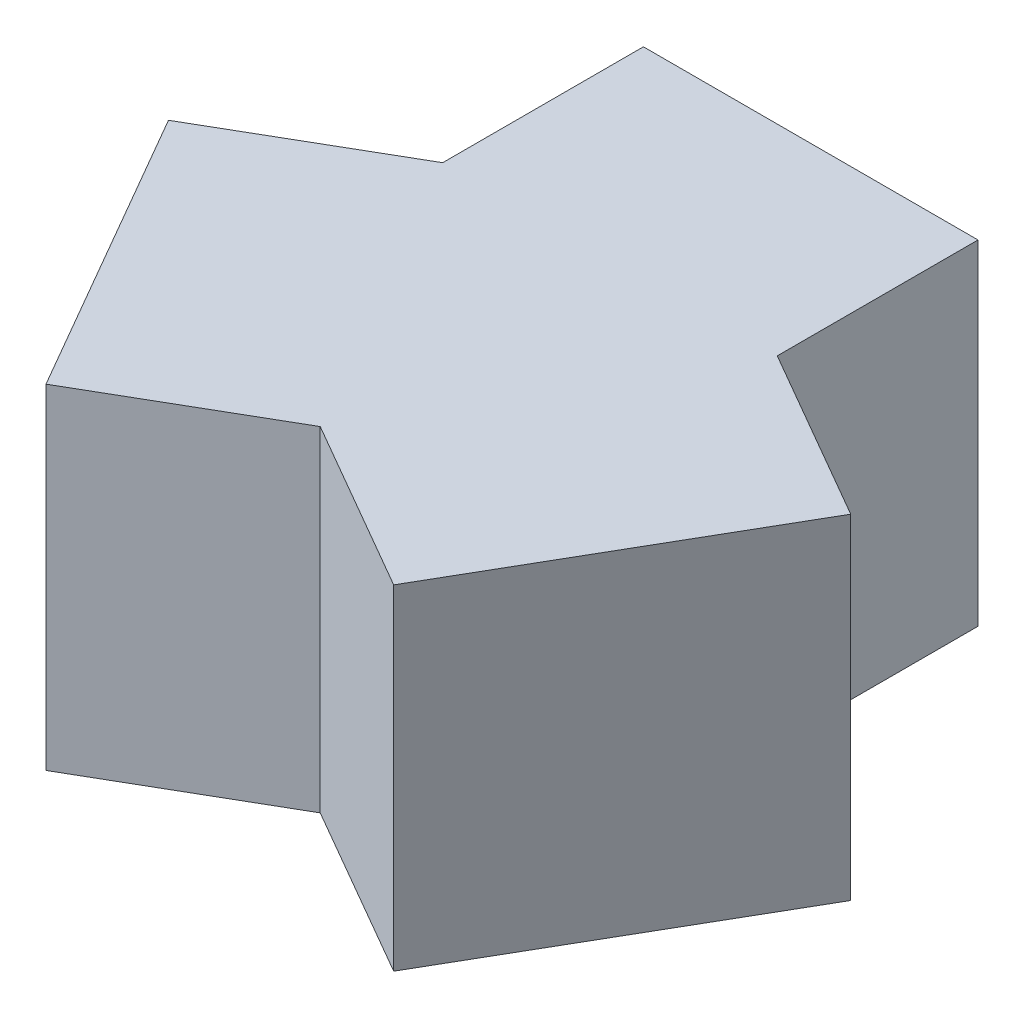
SolidWorks part; units mm, degrees
ref_plane "Front Plane" through (0, 0, 0) normal (0, 0, 1) x (1, 0, 0)
ref_plane "Top Plane" through (0, 0, 0) normal (0, 1, 0) x (1, 0, 0)
ref_plane "Right Plane" through (0, 0, 0) normal (1, 0, 0) x (0, 0, -1)
sketch "Sketch1" plane through (0, 0, 0) normal (0, 1, 0) x (1, 0, 0)
  line L0 (15.2942, 0.5) -> (7.5, 5)
  line L1 (7.5, 5) -> (7.5, 14)
  line L5 (0, -7.9904) -> (7.7942, -12.4904)
  line L7 (7.5, 5) -> (0, -7.9904) construction
  line L8 (7.5, 5) -> (-7.5, 5) construction
  line L9 (-7.5, 14) -> (7.5, 14)
  line L10 (15.2942, 0.5) -> (7.7942, -12.4904)
  line L12 (0, 30.0328) -> (0, -20.7177) construction
  line L13 (-7.5, 5) -> (0, -7.9904) construction
  line L14 (-15.2942, 0.5) -> (-7.7942, -12.4904)
  line L15 (0, -7.9904) -> (-7.7942, -12.4904)
  line L16 (-15.2942, 0.5) -> (-7.5, 5)
  line L17 (-7.5, 5) -> (-7.5, 14)
  point P6 (0, 5)
  point P9 (0, 14)
  dimension "D3" = 15
  dimension "D4" = 9
  dimension "D5" = 9
extrude "Boss-Extrude1" add sketch "Sketch1" along normal mid plane 15
